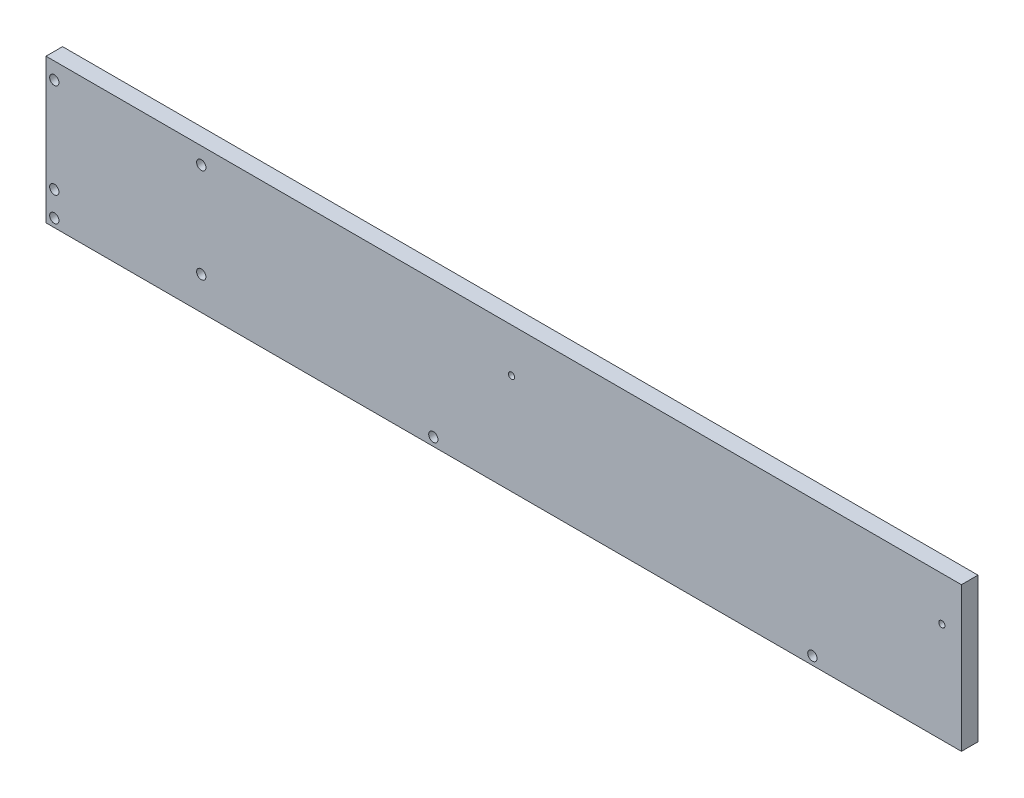
SolidWorks part; units mm, degrees
ref_plane "Front Plane" through (0, 0, 0) normal (0, 0, 1) x (1, 0, 0)
ref_plane "Top Plane" through (0, 0, 0) normal (0, 1, 0) x (1, 0, 0)
ref_plane "Right Plane" through (0, 0, 0) normal (1, 0, 0) x (0, 0, -1)
sketch "Sketch1" plane through (0, 0, 0) normal (0, 0, 1) x (1, 0, 0)
  line B0 (350.99, 55.35) -> (0, 55.35)
  line B1 (350.99, 0) -> (350.99, 55.35)
  line B2 (0, 0) -> (350.99, 0)
  line B3 (0, 55.35) -> (0, 0)
  circle B4 centre (148.5075, 3.175) radius 1.7859
  circle B5 centre (3.175, 12.7) radius 1.7859
  circle B6 centre (3.175, 49) radius 1.7859
  circle B7 centre (3.175, 3.175) radius 1.7859
  circle B8 centre (178.49, 38.5) radius 1.1906
  circle B9 centre (343.49, 38.5) radius 1.1906
  circle B10 centre (293.84, 3.175) radius 1.7859
  circle B11 centre (59.525, 12.7) radius 1.7859
  circle B12 centre (59.525, 49) radius 1.7859
sketch_block_instance "Right_Side_OC-1"
sketch_block "Right_Side_OC"
extrude "Boss-Extrude1" add sketch "Sketch1" along normal blind 6.35
